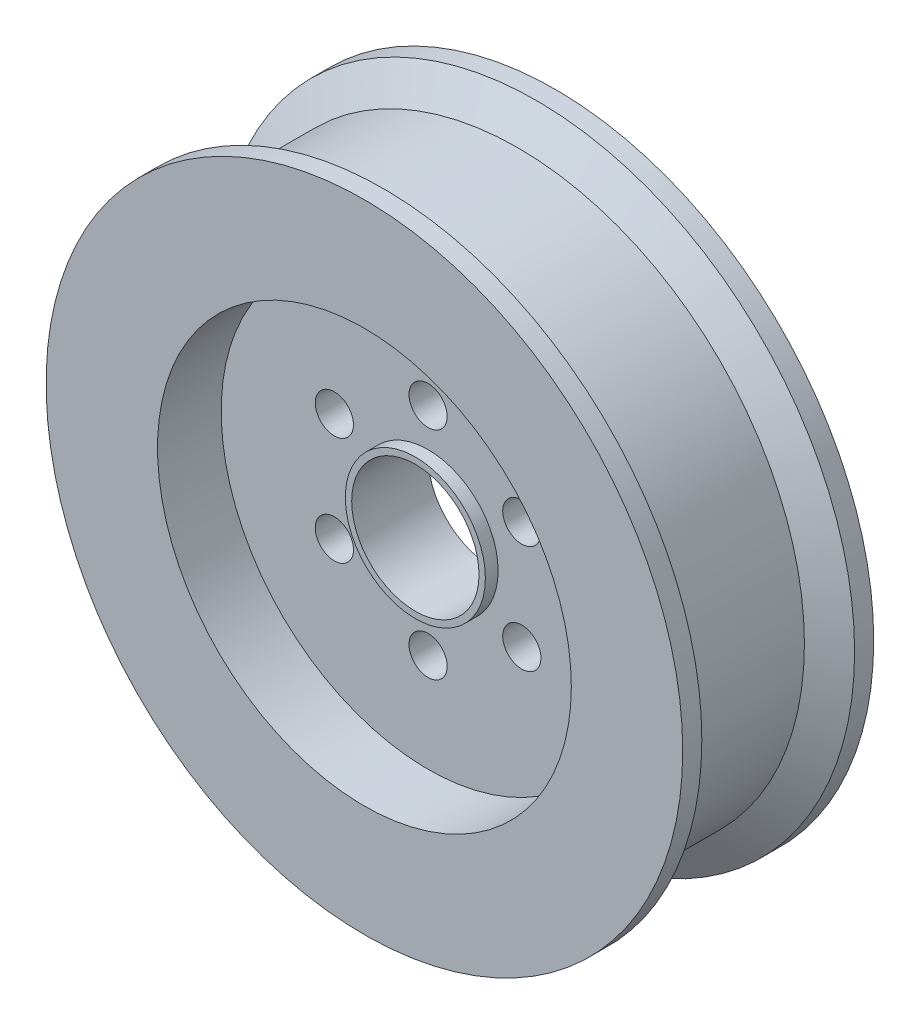
SolidWorks part; units mm, degrees
ref_plane "Front Plane" through (0, 0, 0) normal (0, 0, 1) x (1, 0, 0)
ref_plane "Top Plane" through (0, 0, 0) normal (0, 1, 0) x (1, 0, 0)
ref_plane "Right Plane" through (0, 0, 0) normal (1, 0, 0) x (0, 0, -1)
sketch "Sketch1" plane through (0, 0, 0) normal (0, 0, 1) x (1, 0, 0)
  circle A0 centre (0, 0) radius 50
  circle A1 centre (0, 0) radius 10
  dimension "D1" = 20
  dimension "D2" = 100
extrude "Boss-Extrude1" add sketch "Sketch1" along normal mid plane 30
sketch "Sketch2" plane through (0, 0, 15) normal (0, 0, 1) x (1, 0, 0)
  circle A0 centre (0, 0) radius 32.5
  circle A1 centre (0, 0) radius 50 construction
  dimension "D1" = 17.5
extrude "Cut-Extrude2" cut sketch "Sketch2" against normal blind 10
mirror "Mirror2" about plane through (0, 0, 0) normal (0, 0, 1) of "Cut-Extrude2"
sketch "Sketch3" plane through (0, 0, 5) normal (0, 0, 1) x (1, 0, 0)
  line L0 (0, -1000) -> (0, 49000) construction
  circle A0 centre (0, 17) radius 3
  point P4 (0, 0)
  dimension "D2" = 6
  dimension "D1" = 17
extrude "Cut-Extrude8" cut sketch "Sketch3" against normal blind 10
pattern_circular "CirPattern1" count 6 over 360 about axis through (0, 0, 0) along (0, 0, 1) of "Cut-Extrude8"
sketch "Sketch4" plane through (0, 0, 5) normal (0, 0, 1) x (1, 0, 0)
  circle A0 centre (0, 0) radius 11
  circle A1 centre (0, 0) radius 10 construction
  circle A2 centre (0, 0) radius 10
  dimension "D1" = 22
extrude "Boss-Extrude3" add sketch "Sketch4" along normal blind 2 and the other way blind 7 contours A0 | A2
sketch "Sketch5" plane through (0, 0, 0) normal (0, 1, 0) x (1, 0, 0)
  line L0 (0, 0) -> (0, 21.4107) construction
  line L1 (50, 12) -> (45, 9.1132)
  line L2 (50, -15) -> (50, 15) construction
  line L3 (45, 9.1132) -> (45, -9.1132)
  line L4 (45, -9.1132) -> (50, -12)
  line L5 (50, -12) -> (50, 12)
  line L7 (50, 15) -> (-50, 15) construction
  line L8 (-50, -15) -> (50, -15) construction
  dimension "D1" = 5
  dimension "D2" = 3
  dimension "D3" = 3
  dimension "D4" = 60
  dimension "D5" = 60
revolve "Cut-Revolve2" cut sketch "Sketch5" angle 360 about L0
